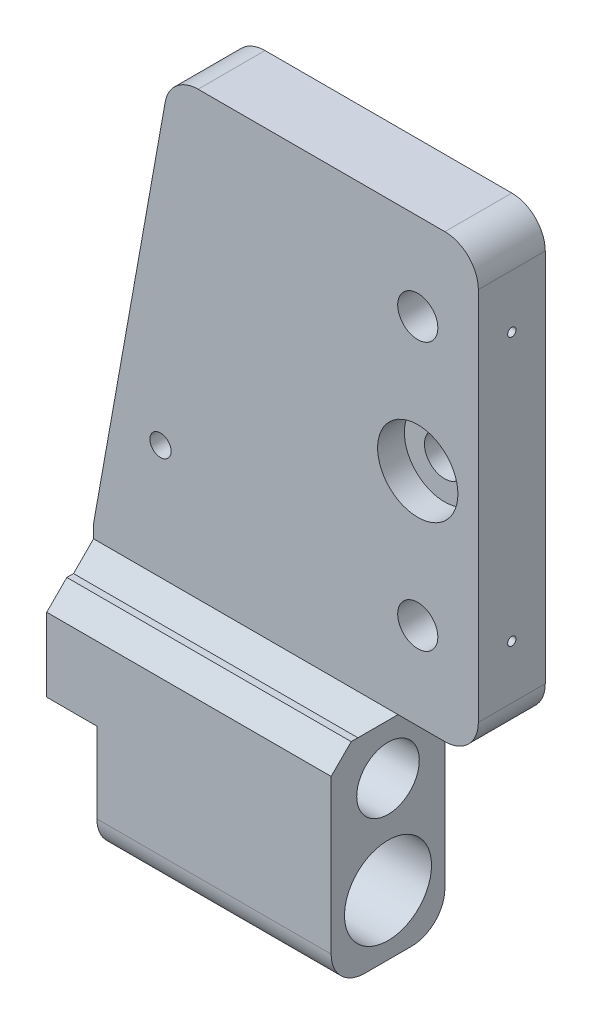
SolidWorks part; units mm, degrees
ref_plane "Front Plane" through (0, 0, 0) normal (0, 0, 1) x (1, 0, 0)
ref_plane "Top Plane" through (0, 0, 0) normal (0, 1, 0) x (1, 0, 0)
ref_plane "Right Plane" through (0, 0, 0) normal (1, 0, 0) x (0, 0, -1)
sketch "Sketch1" plane through (0, 0, 0) normal (0, 0, 1) x (1, 0, 0)
  line L0 (0, 0) -> (70, 0)
  line L1 (70, 0) -> (70, 62)
  line L2 (76, 68) -> (100, 68)
  line L3 (100, 68) -> (100, 200)
  line L4 (100, 200) -> (7.8769, 200)
  line L5 (7.8769, 200) -> (-15, 72)
  line L6 (-15, 72) -> (-15, 34)
  line L7 (-15, 34) -> (0, 34)
  line L8 (0, 34) -> (0, 0)
  line L9 (70, 62) -> (76, 68)
  circle A0 centre (81.8911, 174) radius 6
  circle A1 centre (81.8911, 94) radius 6
  point P4 (70, 68)
  dimension "12" = 12
  dimension "D1" = 70
  dimension "D2" = 68
  dimension "D3" = 200
  dimension "D4" = 30
  dimension "D5" = 92.1231
  dimension "D6" = 15
  dimension "38" = 38
  dimension "D7" = 34
  dimension "D8" = 80
  dimension "26" = 26
  dimension "D9" = 18.1089
extrude "Boss-Extrude1" add sketch "Sketch1" along normal blind 34
sketch "Sketch2" plane through (0, 0, 34) normal (0, 0, 1) x (1, 0, 0)
  line L0 (-15, 72) -> (-15, 34) construction
  line L1 (100, 200) -> (-15, 200)
  line L2 (100, 200) -> (100, 62)
  line L3 (100, 62) -> (-15, 62)
  line L4 (-15, 200) -> (-15, 62)
  dimension "D1" = 138
extrude "Cut-Extrude1" cut sketch "Sketch2" against normal blind 14 contours L2 L1 L4 L3
sketch "Sketch3" plane through (0, 0, 20) normal (0, 0, 1) x (1, 0, 0)
  line L0 (81.8911, 174) -> (81.8911, 94) construction
  circle A0 centre (81.8911, 134) radius 12
  dimension "D1" = 24
extrude "Cut-Extrude2" cut sketch "Sketch3" against normal blind 8
sketch "Sketch4" plane through (0, 0, 12) normal (0, 0, 1) x (1, 0, 0)
  circle A0 centre (81.8911, 134) radius 6
  dimension "D1" = 12
extrude "Cut-Extrude3" cut sketch "Sketch4" against normal through all
fillet "Fillet1" radius 10 3 edges at (100, 68, 10) (100, 200, 10) (7.8769, 200, 10)
chamfer "Chamfer1" distance 6 angle 45 2 edges at (27.5, 62, 34) (27.5, 62, 20)
ref_plane "Plane1" through (0, 0, 17) normal (0, 0, 1) x (1, 0, 0)
sketch "Sketch6" plane through (70, 0, 0) normal (1, 0, 0) x (0, 0, -1)
  line L0 (-34, 0) -> (0, 0) construction
  line L2 (-17, 0) -> (-17, 36)
  circle A0 centre (-17, 18) radius 13
  point P4 (-17, 18)
  dimension "D2" = 26
  dimension "D1" = 18
extrude "Cut-Extrude8" cut sketch "Sketch6" against normal blind 34 contours L2 A0 | L2 A0
sketch "Sketch11" plane through (0, 0, 0) normal (-1, 0, 0) x (0, 0, 1)
  line L0 (34, 0) -> (0, 0) construction
  circle A0 centre (17, 18) radius 11.5
  dimension "D2" = 23
  dimension "D1" = 18
extrude "Cut-Extrude9" cut sketch "Sketch11" against normal blind 6
sketch "Sketch12" plane through (6, 0, 0) normal (-1, 0, 0) x (0, 0, 1)
  circle A0 centre (17, 18) radius 7
  dimension "D1" = 14
extrude "Cut-Extrude10" cut sketch "Sketch12" against normal through all
fillet "Fillet3" radius 10 2 edges at (35, 0, 34) (35, 0, 0)
sketch "Sketch13" plane through (6, 0, 0) normal (-1, 0, 0) x (0, 0, 1)
  line L0 (17, 18) -> (17, 26) construction
  circle A0 centre (17, 26) radius 1.5
  circle A1 centre (25, 18) radius 1.5
  circle A2 centre (17, 10) radius 1.5
  circle A3 centre (9, 18) radius 1.5
  point P13 (17, 18)
  dimension "D1" = 3
  dimension "D2" = 8
  dimension "D3" = 4
extrude "Cut-Extrude11" cut sketch "Sketch13" against normal through all
sketch "Sketch16" plane through (100, 0, 0) normal (1, 0, 0) x (0, 0, -1)
  line L0 (-10, 180) -> (-10, 168) construction
  line L1 (0, 180) -> (-20, 180) construction
  line L2 (-20, 168) -> (0, 168) construction
  line L3 (-10, 100) -> (-10, 88) construction
  line L4 (0, 100) -> (-20, 100) construction
  line L5 (-20, 88) -> (0, 88) construction
  point P0 (-10, 174)
  point P2 (-10, 94)
hole_wizard "M3 Tapped Hole1" positions "Sketch16" profile "Sketch15" tap size "M3" standard "ISO"
sketch "Sketch15" plane through (100, 174, 10) normal (0, 1, 0) x (0, 0, -1)
  line L0 (0, 0) -> (0, 20.7511)
  line L1 (0, 20.7511) -> (1.25, 20)
  line L2 (1.25, 20) -> (1.25, 0)
  line L5 (1.25, 0) -> (0, 0)
  line L10 (0, 20.7511) -> (-1.25, 20) construction
  line L11 (0, -6.35) -> (0, 107.95) construction
  dimension "Tap Drill Dia." = 2.5
  dimension "Tap Drill Depth" = 20
  dimension "Drill Angle" = 118
cosmetic thread "Hole Thread1" parameters "D1"=6, "D2"=3
cosmetic thread "Hole Thread2" parameters "D1"=6, "D2"=3
sketch "Sketch17" plane through (-15, 0, 0) normal (-1, 0, 0) x (0, 0, 1)
  circle A0 centre (17, 47) radius 9.3492
  dimension "D1" = 18.6984
  dimension "D2" = 29
extrude "Cut-Extrude12" cut sketch "Sketch17" against normal through all
sketch "Sketch18" plane through (0, 0, 0) normal (0, 0, -1) x (-1, 0, 0)
  line L0 (15, 72) -> (15, 34) construction
  circle A0 centre (-5, 102.221) radius 3.175
  dimension "D1" = 6.35
  dimension "D2" = 20
extrude "Cut-Extrude13" cut sketch "Sketch18" against normal up to surface (20 mm away) up to face at (93.8911, 134, 20)
